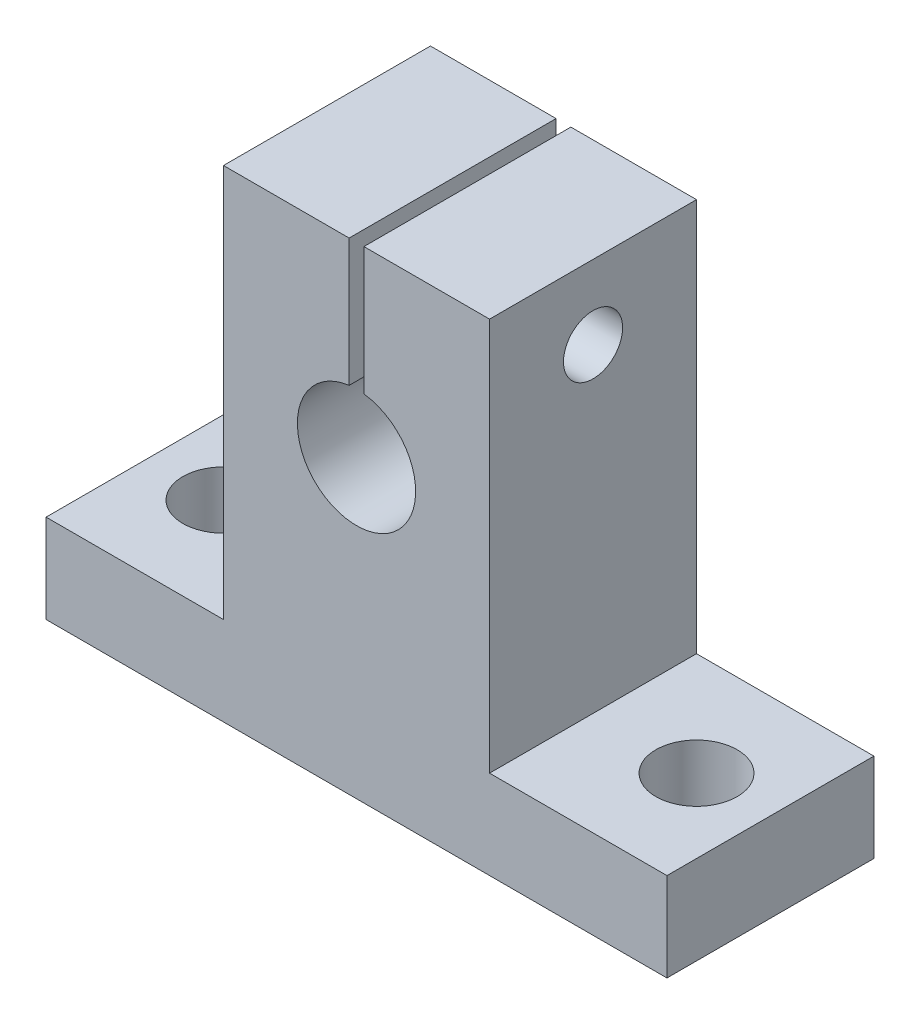
SolidWorks part; units mm, degrees
material "6063-T4"
ref_plane "前视基准面" through (0, 0, 0) normal (0, 0, 1) x (1, 0, 0)
ref_plane "上视基准面" through (0, 0, 0) normal (0, 1, 0) x (1, 0, 0)
ref_plane "右视基准面" through (0, 0, 0) normal (1, 0, 0) x (0, 0, -1)
other "Configuration Table"
sketch "草图1" plane through (0, 0, 0) normal (0, 0, 1) x (1, 0, 0)
  line L0 (0, 0) -> (0, 22.1097) construction
  line L1 (21, 0) -> (-21, 0)
  line L2 (-21, 0) -> (-21, 6)
  line L3 (-21, 6) -> (-9, 6)
  line L4 (-9, 6) -> (-9, 32.6)
  line L5 (-9, 32.6) -> (9, 32.6)
  line L6 (21, 0) -> (21, 6)
  line L7 (21, 6) -> (9, 6)
  line L8 (9, 6) -> (9, 32.6)
  circle A0 centre (0, 20) radius 4
  point P12 (0, 32.6)
  dimension "D5" = 8
  dimension "D1" = 42
  dimension "D2" = 18
  dimension "D3" = 6
  dimension "D4" = 20
  dimension "D6" = 32.6
extrude "凸台-拉伸1" add sketch "草图1" along normal blind 14
sketch "草图2" plane through (0, 6, 0) normal (0, 1, 0) x (1, 0, 0)
  line L0 (0, 0) -> (0, -7.5232) construction
  line L2 (9, 0) -> (-9, 0) construction
  circle A0 centre (16, -7) radius 2.75
  circle A1 centre (-16, -7) radius 2.75
  dimension "D1" = 5.5
  dimension "D2" = 32
extrude "切除-拉伸1" cut sketch "草图2" against normal through all
sketch "草图3" plane through (-9, 0, 0) normal (-1, 0, 0) x (0, 0, 1)
  line L0 (14, 32.6) -> (0, 32.6) construction
  circle A0 centre (7, 27.6) radius 2
  dimension "D1" = 4
  dimension "D2" = 5
extrude "切除-拉伸2" cut sketch "草图3" against normal through all
sketch "草图4" plane through (0, 0, 14) normal (0, 0, 1) x (1, 0, 0)
  line L0 (9, 32.6) -> (-9, 32.6) construction
  line L1 (0.5, 32.6) -> (-0.5, 32.6)
  line L2 (0.5, 32.6) -> (0.5, 23.9686)
  line L3 (0.5, 23.9686) -> (-0.5, 23.9686)
  line L4 (-0.5, 32.6) -> (-0.5, 23.9686)
  line L5 (9, 32.6) -> (-9, 32.6)
  circle A0 centre (0, 20) radius 4 construction
  point P11 (0, 32.6)
  point P12 (0, 32.6)
  dimension "D1" = 1
extrude "切除-拉伸3" cut sketch "草图4" against normal up to next contours L2 L3 L4 L1
